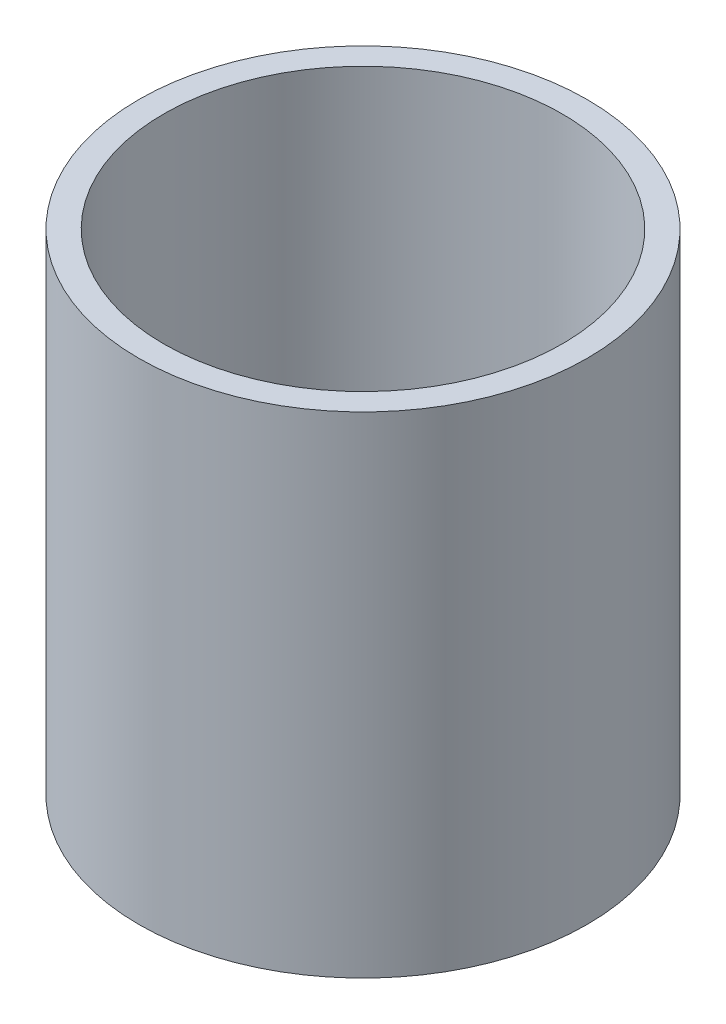
SolidWorks part; units mm, degrees
ref_plane "Front Plane" through (0, 0, 0) normal (0, 0, 1) x (1, 0, 0)
ref_plane "Top Plane" through (0, 0, 0) normal (0, 1, 0) x (1, 0, 0)
ref_plane "Right Plane" through (0, 0, 0) normal (1, 0, 0) x (0, 0, -1)
sketch "Sketch2" plane through (0, 0, 0) normal (0, 1, 0) x (1, 0, 0)
  circle A0 centre (0, 0) radius 20.32
  circle A1 centre (0, 0) radius 22.86
  dimension "D1" = 2.54
extrude "Boss-Extrude1" add sketch "Sketch2" along normal blind 50
